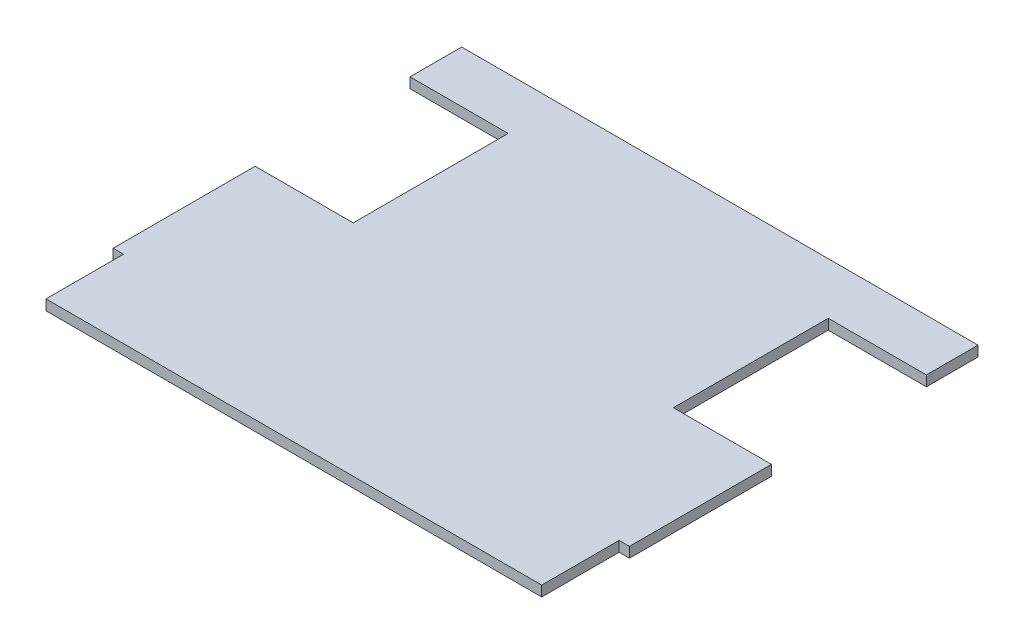
SolidWorks part; units mm, degrees
ref_plane "Alzado" through (0, 0, 0) normal (0, 0, 1) x (1, 0, 0)
ref_plane "Planta" through (0, 0, 0) normal (0, 1, 0) x (1, 0, 0)
ref_plane "Vista lateral" through (0, 0, 0) normal (1, 0, 0) x (0, 0, -1)
sketch "Croquis3" plane through (0, 0, 0) normal (0, 1, 0) x (1, 0, 0)
  line L0 (-190.4327, 32.5) -> (202.9714, 32.5) construction
  line L1 (-100, 82.5) -> (100, 82.5)
  line L2 (-100, 82.5) -> (-100, -82.5)
  line L3 (-100, -82.5) -> (100, -82.5)
  line L4 (100, 82.5) -> (100, -82.5)
  line L5 (-100, 82.5) -> (100, -82.5) construction
  line L6 (-100, -82.5) -> (100, 82.5) construction
  line L7 (0, 144.1781) -> (0, -169.0183) construction
  line L8 (100, 62.5) -> (62, 62.5)
  line L13 (-100, 2.5) -> (-62, 2.5)
  line L14 (-100, 2.5) -> (-100, 62.5)
  line L15 (-100, 62.5) -> (-62, 62.5)
  line L16 (-62, 2.5) -> (-62, 62.5)
  line L17 (62, 2.5) -> (62, 62.5)
  line L18 (100, 2.5) -> (62, 2.5)
  line L19 (100, 2.5) -> (100, 62.5)
  point P0 (0, 0)
  dimension "D1" = 165
  dimension "D2" = 200
  dimension "D3" = 50
  dimension "D4" = 100
  dimension "D5" = 38
  dimension "D6" = 60
  dimension "D7" = 30
extrude "Saliente-Extruir1" add sketch "Croquis3" along normal blind 4 contours L4 L18 L17 L8 L1 L2 L15 L16 L13 L3
sketch "Croquis4" plane through (0, 4, 0) normal (0, 1, 0) x (1, 0, 0)
  line L0 (100, 2.5) -> (100, -82.5) construction
  line L1 (100, -52.5) -> (96, -52.5)
  line L2 (100, -52.5) -> (100, -82.5)
  line L3 (100, -82.5) -> (96, -82.5)
  line L4 (96, -52.5) -> (96, -82.5)
  line L5 (-100, -82.5) -> (100, -82.5) construction
  line L6 (0, 0) -> (0, -82.5) construction
  line L7 (-100, 82.5) -> (100, 82.5) construction
  line L8 (-100, -82.5) -> (-96, -82.5)
  line L9 (-100, -52.5) -> (-100, -82.5)
  line L10 (-100, -52.5) -> (-96, -52.5)
  line L11 (-96, -52.5) -> (-96, -82.5)
  dimension "D1" = 135
  dimension "D2" = 4
extrude "Cortar-Extruir1" cut sketch "Croquis4" against normal up to next
